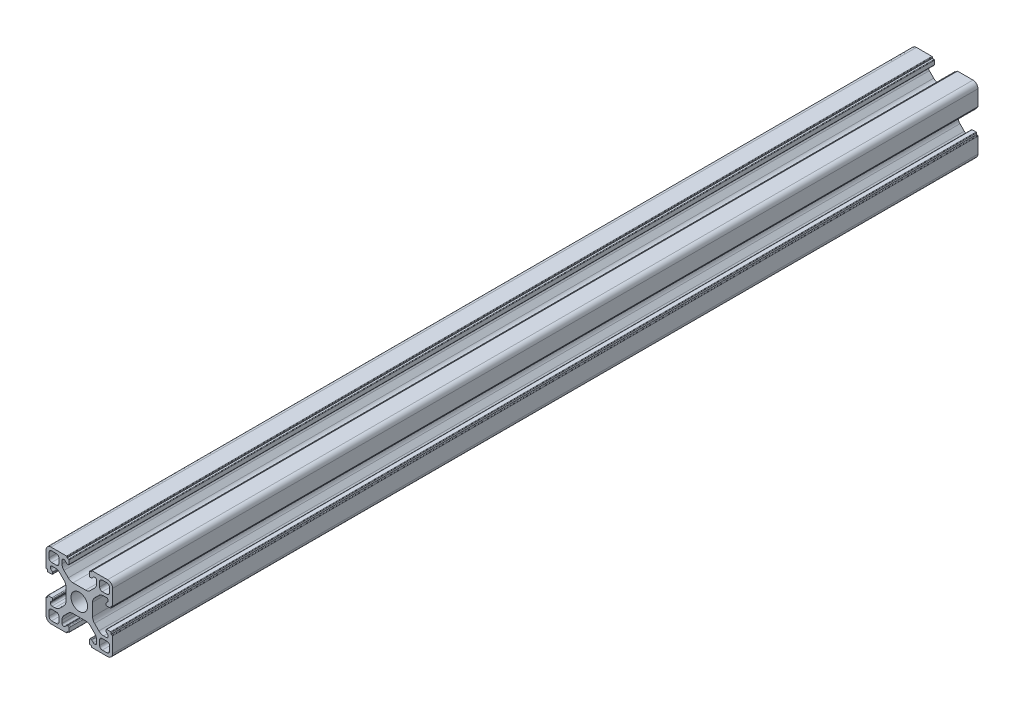
SolidWorks part; units mm, degrees
material "1060 Сплав"
ref_plane "Спереди" through (0, 0, 0) normal (0, 0, 1) x (1, 0, 0)
ref_plane "Сверху" through (0, 0, 0) normal (0, 1, 0) x (1, 0, 0)
ref_plane "Справа" through (0, 0, 0) normal (1, 0, 0) x (0, 0, -1)
sketch "Эскиз1" plane through (0, 0, 0) normal (0, 0, 1) x (1, 0, 0)
  line L0 (-22.0052, 70.3096) -> (-25.0052, 67.3096) construction
  line L1 (-31.1052, 65.2096) -> (-29.2064, 65.2096)
  line L2 (-31.1052, 61.2096) -> (-21.1052, 71.2096) construction
  line L3 (-23.5052, 68.8096) -> (-25.0052, 70.3096) construction
  line L4 (-27.7922, 65.7954) -> (-26.4909, 67.0967)
  line L5 (-24.2052, 67.3096) -> (-22.8052, 67.3096)
  line L6 (-25.0052, 68.1096) -> (-25.0052, 69.5096)
  line L7 (-22.8052, 70.3096) -> (-24.2052, 70.3096)
  line L8 (-25.9052, 69.4096) -> (-25.9052, 68.5109)
  line L9 (-27.3419, 69.2829) -> (-26.8616, 69.7632)
  line L10 (-27.9052, 70.7587) -> (-27.4052, 70.7587)
  line L11 (-27.5187, 69.2096) -> (-27.8052, 69.2096)
  line L12 (-26.508, 69.9096) -> (-26.4052, 69.9096)
  line L13 (-27.4052, 71.0596) -> (-27.4052, 70.7587)
  line L14 (-28.0552, 70.6087) -> (-28.0552, 69.4596)
  line L15 (-22.6052, 71.2096) -> (-27.2552, 71.2096)
  line L16 (-22.0052, 69.5096) -> (-22.0052, 68.1096)
  line L17 (-21.1052, 69.7096) -> (-21.1052, 65.0596)
  line L18 (-21.7061, 64.2596) -> (-22.8552, 64.2596)
  line L19 (-21.2552, 64.9096) -> (-21.5561, 64.9096)
  line L20 (-22.4052, 65.8068) -> (-22.4052, 65.9096)
  line L21 (-23.1052, 64.7961) -> (-23.1052, 64.5096)
  line L22 (-21.5561, 64.4096) -> (-21.5561, 64.9096)
  line L23 (-23.0319, 64.9729) -> (-22.5516, 65.4532)
  line L24 (-22.9052, 66.4096) -> (-23.8039, 66.4096)
  line L25 (-26.5194, 64.5226) -> (-25.2181, 65.8239)
  line L26 (-27.1052, 61.2096) -> (-27.1052, 63.1084)
  line L27 (-27.1052, 61.2096) -> (-27.1052, 59.3109)
  line L28 (-26.5194, 57.8967) -> (-25.2181, 56.5954)
  line L29 (-25.0052, 54.3096) -> (-25.0052, 52.9096)
  line L30 (-24.2052, 55.1096) -> (-22.8052, 55.1096)
  line L31 (-22.0052, 52.9096) -> (-22.0052, 54.3096)
  line L32 (-22.9052, 56.0096) -> (-23.8039, 56.0096)
  line L33 (-23.0319, 57.4464) -> (-22.5516, 56.9661)
  line L34 (-21.5561, 58.0096) -> (-21.5561, 57.5096)
  line L35 (-23.1052, 57.6232) -> (-23.1052, 57.9096)
  line L36 (-22.4052, 56.6125) -> (-22.4052, 56.5096)
  line L37 (-21.2552, 57.5096) -> (-21.5561, 57.5096)
  line L38 (-21.7061, 58.1596) -> (-22.8552, 58.1596)
  line L39 (-21.1052, 52.7096) -> (-21.1052, 57.3596)
  line L40 (-22.8052, 52.1096) -> (-24.2052, 52.1096)
  line L41 (-22.6052, 51.2096) -> (-27.2552, 51.2096)
  line L42 (-28.0552, 51.8106) -> (-28.0552, 52.9596)
  line L43 (-27.4052, 51.3596) -> (-27.4052, 51.6606)
  line L44 (-26.508, 52.5096) -> (-26.4052, 52.5096)
  line L45 (-27.5187, 53.2096) -> (-27.8052, 53.2096)
  line L46 (-27.9052, 51.6606) -> (-27.4052, 51.6606)
  line L47 (-27.3419, 53.1364) -> (-26.8616, 52.6561)
  line L48 (-25.9052, 53.0096) -> (-25.9052, 53.9084)
  line L49 (-27.7922, 56.6239) -> (-26.4909, 55.3226)
  line L50 (-31.1052, 57.2096) -> (-29.2064, 57.2096)
  line L51 (-22.0052, 52.1096) -> (-25.0052, 55.1096) construction
  line L52 (-31.1052, 61.2096) -> (-21.1052, 51.2096) construction
  line L53 (-23.5052, 53.6096) -> (-22.0052, 55.1096) construction
  line L54 (-31.1052, 57.2096) -> (-33.0039, 57.2096)
  line L55 (-34.4181, 56.6239) -> (-35.7194, 55.3226)
  line L56 (-38.0052, 55.1096) -> (-39.4052, 55.1096)
  line L57 (-37.2052, 54.3096) -> (-37.2052, 52.9096)
  line L58 (-39.4052, 52.1096) -> (-38.0052, 52.1096)
  line L59 (-36.3052, 53.0096) -> (-36.3052, 53.9084)
  line L60 (-34.8684, 53.1364) -> (-35.3487, 52.6561)
  line L61 (-34.3052, 51.6606) -> (-34.8052, 51.6606)
  line L62 (-34.6916, 53.2096) -> (-34.4052, 53.2096)
  line L63 (-35.7023, 52.5096) -> (-35.8052, 52.5096)
  line L64 (-34.8052, 51.3596) -> (-34.8052, 51.6606)
  line L65 (-34.1552, 51.8106) -> (-34.1552, 52.9596)
  line L66 (-39.6052, 51.2096) -> (-34.9552, 51.2096)
  line L67 (-40.2052, 52.9096) -> (-40.2052, 54.3096)
  line L68 (-41.1052, 52.7096) -> (-41.1052, 57.3596)
  line L69 (-40.5042, 58.1596) -> (-39.3552, 58.1596)
  line L70 (-40.9552, 57.5096) -> (-40.6542, 57.5096)
  line L71 (-39.8052, 56.6125) -> (-39.8052, 56.5096)
  line L72 (-39.1052, 57.6232) -> (-39.1052, 57.9096)
  line L73 (-40.6542, 58.0096) -> (-40.6542, 57.5096)
  line L74 (-39.1784, 57.4464) -> (-39.6587, 56.9661)
  line L75 (-39.3052, 56.0096) -> (-38.4064, 56.0096)
  line L76 (-35.6909, 57.8967) -> (-36.9922, 56.5954)
  line L77 (-35.1052, 61.2096) -> (-35.1052, 59.3109)
  line L78 (-40.2052, 52.1096) -> (-37.2052, 55.1096) construction
  line L79 (-31.1052, 61.2096) -> (-41.1052, 51.2096) construction
  line L80 (-38.7052, 53.6096) -> (-37.2052, 52.1096) construction
  line L81 (-35.1052, 61.2096) -> (-35.1052, 63.1084)
  line L82 (-35.6909, 64.5226) -> (-36.9922, 65.8239)
  line L83 (-37.2052, 68.1096) -> (-37.2052, 69.5096)
  line L84 (-38.0052, 67.3096) -> (-39.4052, 67.3096)
  line L85 (-40.2052, 69.5096) -> (-40.2052, 68.1096)
  line L86 (-39.3052, 66.4096) -> (-38.4064, 66.4096)
  line L87 (-39.1784, 64.9729) -> (-39.6587, 65.4532)
  line L88 (-40.6542, 64.4096) -> (-40.6542, 64.9096)
  line L89 (-39.1052, 64.7961) -> (-39.1052, 64.5096)
  line L90 (-39.8052, 65.8068) -> (-39.8052, 65.9096)
  line L91 (-40.9552, 64.9096) -> (-40.6542, 64.9096)
  line L92 (-40.5042, 64.2596) -> (-39.3552, 64.2596)
  line L93 (-41.1052, 69.7096) -> (-41.1052, 65.0596)
  line L94 (-39.4052, 70.3096) -> (-38.0052, 70.3096)
  line L95 (-39.6052, 71.2096) -> (-34.9552, 71.2096)
  line L96 (-34.1552, 70.6087) -> (-34.1552, 69.4596)
  line L97 (-34.8052, 71.0596) -> (-34.8052, 70.7587)
  line L98 (-35.7023, 69.9096) -> (-35.8052, 69.9096)
  line L99 (-34.6916, 69.2096) -> (-34.4052, 69.2096)
  line L100 (-34.3052, 70.7587) -> (-34.8052, 70.7587)
  line L101 (-34.8684, 69.2829) -> (-35.3487, 69.7632)
  line L102 (-36.3052, 69.4096) -> (-36.3052, 68.5109)
  line L103 (-34.4181, 65.7954) -> (-35.7194, 67.0967)
  line L104 (-31.1052, 65.2096) -> (-33.0039, 65.2096)
  line L105 (-42.8692, 61.2096) -> (-19.6008, 61.2096) construction
  line L106 (-40.2052, 70.3096) -> (-37.2052, 67.3096) construction
  line L107 (-31.1052, 49.1232) -> (-31.1052, 71.9286) construction
  line L108 (-31.1052, 61.2096) -> (-41.1052, 71.2096) construction
  line L109 (-38.7052, 68.8096) -> (-40.2052, 67.3096) construction
  arc A0 (-22.0052, 69.5096) -> (-22.8052, 70.3096) centre (-22.8052, 69.5096) ccw
  arc A1 (-24.2052, 70.3096) -> (-25.0052, 69.5096) centre (-24.2052, 69.5096) ccw
  arc A2 (-24.2052, 67.3096) -> (-25.0052, 68.1096) centre (-24.2052, 68.1096) cw
  arc A3 (-22.6052, 71.2096) -> (-21.1052, 69.7096) centre (-22.6052, 69.7096) cw
  arc A4 (-27.9052, 70.7587) -> (-28.0552, 70.6087) centre (-27.9052, 70.6087) ccw
  arc A5 (-27.2552, 71.2096) -> (-27.4052, 71.0596) centre (-27.2552, 71.0596) ccw
  arc A6 (-27.5187, 69.2096) -> (-27.3419, 69.2829) centre (-27.5187, 69.4596) ccw
  arc A7 (-27.8052, 69.2096) -> (-28.0552, 69.4596) centre (-27.8052, 69.4596) cw
  arc A8 (-26.8616, 69.7632) -> (-26.508, 69.9096) centre (-26.508, 69.4096) cw
  arc A9 (-26.4052, 69.9096) -> (-25.9052, 69.4096) centre (-26.4052, 69.4096) cw
  arc A10 (-28.6052, 61.2096) -> (-31.1052, 63.7096) centre (-31.1052, 61.2096) ccw
  arc A11 (-29.2064, 65.2096) -> (-27.7922, 65.7954) centre (-29.2064, 67.2096) ccw
  arc A12 (-25.9052, 68.5109) -> (-26.4909, 67.0967) centre (-27.9052, 68.5109) cw
  arc A13 (-22.0052, 68.1096) -> (-22.8052, 67.3096) centre (-22.8052, 68.1096) cw
  arc A14 (-22.4052, 65.9096) -> (-22.9052, 66.4096) centre (-22.9052, 65.9096) ccw
  arc A15 (-22.5516, 65.4532) -> (-22.4052, 65.8068) centre (-22.9052, 65.8068) ccw
  arc A16 (-23.1052, 64.5096) -> (-22.8552, 64.2596) centre (-22.8552, 64.5096) ccw
  arc A17 (-23.1052, 64.7961) -> (-23.0319, 64.9729) centre (-22.8552, 64.7961) cw
  arc A18 (-21.1052, 65.0596) -> (-21.2552, 64.9096) centre (-21.2552, 65.0596) cw
  arc A19 (-21.5561, 64.4096) -> (-21.7061, 64.2596) centre (-21.7061, 64.4096) cw
  arc A20 (-23.8039, 66.4096) -> (-25.2181, 65.8239) centre (-23.8039, 64.4096) ccw
  arc A21 (-27.1052, 63.1084) -> (-26.5194, 64.5226) centre (-25.1052, 63.1084) cw
  arc A22 (-22.8052, 52.1096) -> (-22.0052, 52.9096) centre (-22.8052, 52.9096) ccw
  arc A23 (-22.0052, 54.3096) -> (-22.8052, 55.1096) centre (-22.8052, 54.3096) ccw
  arc A24 (-25.0052, 54.3096) -> (-24.2052, 55.1096) centre (-24.2052, 54.3096) cw
  arc A25 (-21.1052, 52.7096) -> (-22.6052, 51.2096) centre (-22.6052, 52.7096) cw
  arc A26 (-21.5561, 58.0096) -> (-21.7061, 58.1596) centre (-21.7061, 58.0096) ccw
  arc A27 (-21.1052, 57.3596) -> (-21.2552, 57.5096) centre (-21.2552, 57.3596) ccw
  arc A28 (-23.1052, 57.6232) -> (-23.0319, 57.4464) centre (-22.8552, 57.6232) ccw
  arc A29 (-23.1052, 57.9096) -> (-22.8552, 58.1596) centre (-22.8552, 57.9096) cw
  arc A30 (-22.5516, 56.9661) -> (-22.4052, 56.6125) centre (-22.9052, 56.6125) cw
  arc A31 (-22.4052, 56.5096) -> (-22.9052, 56.0096) centre (-22.9052, 56.5096) cw
  arc A32 (-31.1052, 58.7096) -> (-28.6052, 61.2096) centre (-31.1052, 61.2096) ccw
  arc A33 (-27.1052, 59.3109) -> (-26.5194, 57.8967) centre (-25.1052, 59.3109) ccw
  arc A34 (-23.8039, 56.0096) -> (-25.2181, 56.5954) centre (-23.8039, 58.0096) cw
  arc A35 (-24.2052, 52.1096) -> (-25.0052, 52.9096) centre (-24.2052, 52.9096) cw
  arc A36 (-26.4052, 52.5096) -> (-25.9052, 53.0096) centre (-26.4052, 53.0096) ccw
  arc A37 (-26.8616, 52.6561) -> (-26.508, 52.5096) centre (-26.508, 53.0096) ccw
  arc A38 (-27.8052, 53.2096) -> (-28.0552, 52.9596) centre (-27.8052, 52.9596) ccw
  arc A39 (-27.5187, 53.2096) -> (-27.3419, 53.1364) centre (-27.5187, 52.9596) cw
  arc A40 (-27.2552, 51.2096) -> (-27.4052, 51.3596) centre (-27.2552, 51.3596) cw
  arc A41 (-27.9052, 51.6606) -> (-28.0552, 51.8106) centre (-27.9052, 51.8106) cw
  arc A42 (-25.9052, 53.9084) -> (-26.4909, 55.3226) centre (-27.9052, 53.9084) ccw
  arc A43 (-29.2064, 57.2096) -> (-27.7922, 56.6239) centre (-29.2064, 55.2096) cw
  arc A44 (-40.2052, 52.9096) -> (-39.4052, 52.1096) centre (-39.4052, 52.9096) ccw
  arc A45 (-38.0052, 52.1096) -> (-37.2052, 52.9096) centre (-38.0052, 52.9096) ccw
  arc A46 (-38.0052, 55.1096) -> (-37.2052, 54.3096) centre (-38.0052, 54.3096) cw
  arc A47 (-39.6052, 51.2096) -> (-41.1052, 52.7096) centre (-39.6052, 52.7096) cw
  arc A48 (-34.3052, 51.6606) -> (-34.1552, 51.8106) centre (-34.3052, 51.8106) ccw
  arc A49 (-34.9552, 51.2096) -> (-34.8052, 51.3596) centre (-34.9552, 51.3596) ccw
  arc A50 (-34.6916, 53.2096) -> (-34.8684, 53.1364) centre (-34.6916, 52.9596) ccw
  arc A51 (-34.4052, 53.2096) -> (-34.1552, 52.9596) centre (-34.4052, 52.9596) cw
  arc A52 (-35.3487, 52.6561) -> (-35.7023, 52.5096) centre (-35.7023, 53.0096) cw
  arc A53 (-35.8052, 52.5096) -> (-36.3052, 53.0096) centre (-35.8052, 53.0096) cw
  arc A54 (-33.6052, 61.2096) -> (-31.1052, 58.7096) centre (-31.1052, 61.2096) ccw
  arc A55 (-33.0039, 57.2096) -> (-34.4181, 56.6239) centre (-33.0039, 55.2096) ccw
  arc A56 (-36.3052, 53.9084) -> (-35.7194, 55.3226) centre (-34.3052, 53.9084) cw
  arc A57 (-40.2052, 54.3096) -> (-39.4052, 55.1096) centre (-39.4052, 54.3096) cw
  arc A58 (-39.8052, 56.5096) -> (-39.3052, 56.0096) centre (-39.3052, 56.5096) ccw
  arc A59 (-39.6587, 56.9661) -> (-39.8052, 56.6125) centre (-39.3052, 56.6125) ccw
  arc A60 (-39.1052, 57.9096) -> (-39.3552, 58.1596) centre (-39.3552, 57.9096) ccw
  arc A61 (-39.1052, 57.6232) -> (-39.1784, 57.4464) centre (-39.3552, 57.6232) cw
  arc A62 (-41.1052, 57.3596) -> (-40.9552, 57.5096) centre (-40.9552, 57.3596) cw
  arc A63 (-40.6542, 58.0096) -> (-40.5042, 58.1596) centre (-40.5042, 58.0096) cw
  arc A64 (-38.4064, 56.0096) -> (-36.9922, 56.5954) centre (-38.4064, 58.0096) ccw
  arc A65 (-35.1052, 59.3109) -> (-35.6909, 57.8967) centre (-37.1052, 59.3109) cw
  arc A66 (-39.4052, 70.3096) -> (-40.2052, 69.5096) centre (-39.4052, 69.5096) ccw
  arc A67 (-40.2052, 68.1096) -> (-39.4052, 67.3096) centre (-39.4052, 68.1096) ccw
  arc A68 (-37.2052, 68.1096) -> (-38.0052, 67.3096) centre (-38.0052, 68.1096) cw
  arc A69 (-41.1052, 69.7096) -> (-39.6052, 71.2096) centre (-39.6052, 69.7096) cw
  arc A70 (-40.6542, 64.4096) -> (-40.5042, 64.2596) centre (-40.5042, 64.4096) ccw
  arc A71 (-41.1052, 65.0596) -> (-40.9552, 64.9096) centre (-40.9552, 65.0596) ccw
  arc A72 (-39.1052, 64.7961) -> (-39.1784, 64.9729) centre (-39.3552, 64.7961) ccw
  arc A73 (-39.1052, 64.5096) -> (-39.3552, 64.2596) centre (-39.3552, 64.5096) cw
  arc A74 (-39.6587, 65.4532) -> (-39.8052, 65.8068) centre (-39.3052, 65.8068) cw
  arc A75 (-39.8052, 65.9096) -> (-39.3052, 66.4096) centre (-39.3052, 65.9096) cw
  arc A76 (-31.1052, 63.7096) -> (-33.6052, 61.2096) centre (-31.1052, 61.2096) ccw
  arc A77 (-35.1052, 63.1084) -> (-35.6909, 64.5226) centre (-37.1052, 63.1084) ccw
  arc A78 (-38.4064, 66.4096) -> (-36.9922, 65.8239) centre (-38.4064, 64.4096) cw
  arc A79 (-38.0052, 70.3096) -> (-37.2052, 69.5096) centre (-38.0052, 69.5096) cw
  arc A80 (-35.8052, 69.9096) -> (-36.3052, 69.4096) centre (-35.8052, 69.4096) ccw
  arc A81 (-35.3487, 69.7632) -> (-35.7023, 69.9096) centre (-35.7023, 69.4096) ccw
  arc A82 (-34.4052, 69.2096) -> (-34.1552, 69.4596) centre (-34.4052, 69.4596) ccw
  arc A83 (-34.6916, 69.2096) -> (-34.8684, 69.2829) centre (-34.6916, 69.4596) cw
  arc A84 (-34.9552, 71.2096) -> (-34.8052, 71.0596) centre (-34.9552, 71.0596) cw
  arc A85 (-34.3052, 70.7587) -> (-34.1552, 70.6087) centre (-34.3052, 70.6087) cw
  arc A86 (-36.3052, 68.5109) -> (-35.7194, 67.0967) centre (-34.3052, 68.5109) ccw
  arc A87 (-33.0039, 65.2096) -> (-34.4181, 65.7954) centre (-33.0039, 67.2096) cw
  point P0 (-31.1052, 61.2096)
  point P9 (-31.1052, 61.2096)
  point P40 (-22.4052, 64.9096)
  point P93 (-27.4052, 52.5096)
  point P144 (-27.4052, 69.9096)
  point P152 (-22.4052, 57.5096)
  point P153 (-31.1052, 57.2854)
  point P154 (-31.1052, 61.2096)
  point P189 (-39.8052, 57.5096)
  point P228 (-34.8052, 52.5096)
  point P229 (-35.0294, 61.2096)
  point P230 (-31.1052, 61.2096)
  point P268 (-34.8052, 69.9096)
  point P273 (-27.1809, 61.2096)
  point P306 (-39.8052, 64.9096)
  point P307 (-31.1052, 65.1339)
  point P309 (-31.1052, 61.2096)
  dimension "D3" = 5
  dimension "D6" = 2
  dimension "D1" = 2
  dimension "D2" = 6
  dimension "D4" = 4
  dimension "D5" = 0.9
extrude "Бобышка-Вытянуть1" add sketch "Эскиз1" along normal blind 260
